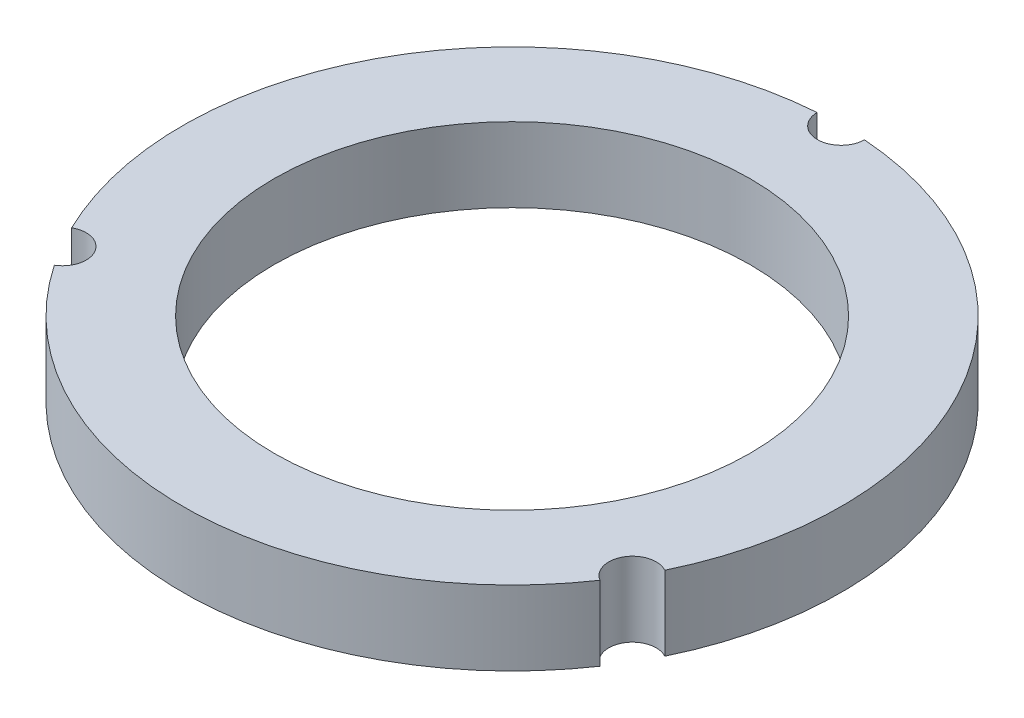
SolidWorks part; units mm, degrees
ref_plane "Front Plane" through (0, 0, 0) normal (0, 0, 1) x (1, 0, 0)
ref_plane "Top Plane" through (0, 0, 0) normal (0, 1, 0) x (1, 0, 0)
ref_plane "Right Plane" through (0, 0, 0) normal (1, 0, 0) x (0, 0, -1)
sketch "Sketch1" plane through (0, 0, 0) normal (0, 1, 0) x (1, 0, 0)
  circle A0 centre (0, 0) radius 10
  circle A1 centre (0, 0) radius 7.22
  dimension "D1" = 20
  dimension "D2" = 14.44
extrude "Boss-Extrude1" add sketch "Sketch1" along normal blind 2.26
sketch "Sketch2" plane through (0, 2.26, 0) normal (0, 1, 0) x (1, 0, 0)
  line L0 (0, 14.7496) -> (0, -18.1459) construction
  circle A0 centre (8.6484, -4.9932) radius 0.72
  circle A2 centre (0, 9.9864) radius 0.72
  circle A3 centre (-8.6484, -4.9932) radius 0.72
  point P12 (0, 0)
  dimension "D1" = 3
  dimension "D2" = 1.44
  dimension "D3" = 9.9864
extrude "Cut-Extrude1" cut sketch "Sketch2" against normal through all
